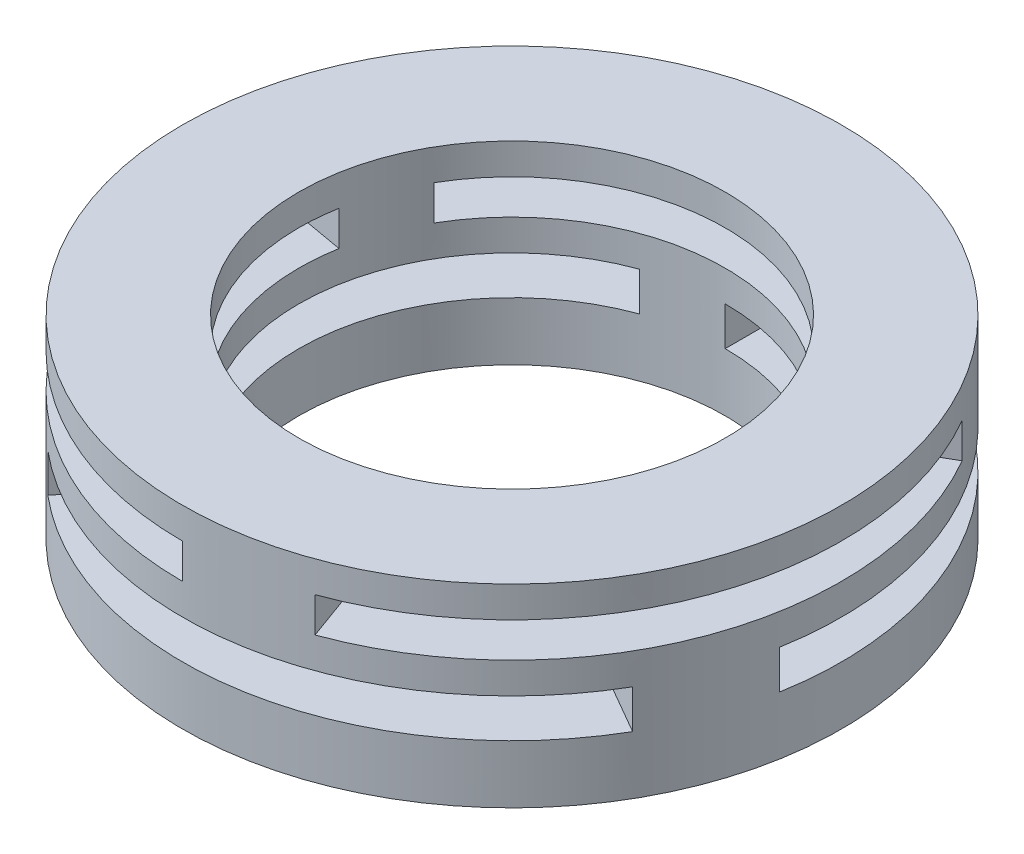
SolidWorks part; units mm, degrees
ref_plane "Plano frontal" through (0, 0, 0) normal (0, 0, 1) x (1, 0, 0)
ref_plane "Plano superior" through (0, 0, 0) normal (0, 1, 0) x (1, 0, 0)
ref_plane "Plano direito" through (0, 0, 0) normal (1, 0, 0) x (0, 0, -1)
sketch "Esboço9" plane through (0, 0, 0) normal (0, 0, 1) x (1, 0, 0)
  line L0 (0, -112.7601) -> (0, 5525.2437) construction
  line L1 (5.5, 0) -> (8.5, 0)
  line L2 (8.5, 0) -> (8.5, 5)
  line L3 (8.5, 5) -> (5.5, 5)
  line L4 (5.5, 5) -> (5.5, 0)
  dimension "D1" = 5.5
  dimension "D2" = 3
  dimension "D3" = 5
revolve "Revolução1" add sketch "Esboço9" angle 360 about L0
ref_plane "Plano4" through (0, 1.5, 0) normal (0, 1, 0) x (1, 0, 0)
sketch "Esboço12" plane through (0, 1.5, 0) normal (0, 1, 0) x (1, 0, 0)
  line L0 (0, 8.5) -> (0, 5.5)
  line L1 (5.4164, -0.9551) -> (8.3709, -1.476)
  circle A0 centre (0, 0) radius 8.5 construction
  arc A1 (8.3709, -1.476) -> (0, 8.5) centre (0, 0) ccw
  arc A2 (5.4164, -0.9551) -> (0, 5.5) centre (0, 0) ccw
  dimension "D1" = 100
extrude "Corte-extrusão1" cut sketch "Esboço12" along normal blind 1
pattern_circular "PadrãoCircular2" count 3 over 360 about axis through (0, 0, 0) along (0, 1, 0) of "Corte-extrusão1"
ref_plane "Plano5" through (0, 3.3, 0) normal (0, 1, 0) x (1, 0, 0)
sketch "Esboço13" plane through (0, 3.3, 0) normal (0, 1, 0) x (1, 0, 0)
  line L0 (0, 0) -> (0, 8.5) construction
  line L1 (0, 0) -> (7.3612, 4.25)
  line L2 (0, 0) -> (2.9072, -7.9874)
  arc A0 (2.9072, -7.9874) -> (7.3612, 4.25) centre (0, 0) ccw
  circle A2 centre (0, 0) radius 8.5 construction
  dimension "D1" = 60
  dimension "D2" = 100
extrude "Corte-extrusão3" cut sketch "Esboço13" along normal blind 0.9
pattern_circular "PadrãoCircular4" count 3 over 360 about axis through (0, 0, 0) along (0, 1, 0) of "Corte-extrusão3"
